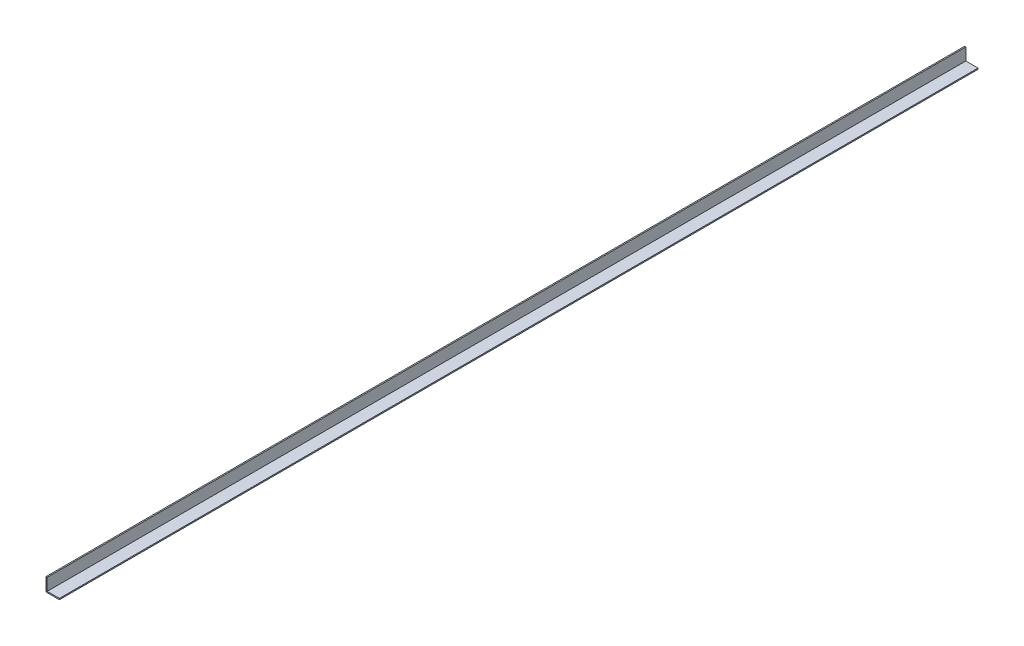
SolidWorks part; units mm, degrees
material "ASTM A36 Acero"
ref_plane "Alzado" through (0, 0, 0) normal (0, 0, 1) x (1, 0, 0)
ref_plane "Planta" through (0, 0, 0) normal (0, 1, 0) x (1, 0, 0)
ref_plane "Vista lateral" through (0, 0, 0) normal (1, 0, 0) x (0, 0, -1)
sketch "Croquis1" plane through (0, 0, 0) normal (0, 0, 1) x (1, 0, 0)
  line L0 (0, 88.9) -> (0, 0)
  line L1 (0, 0) -> (88.9, 0)
  line L2 (88.9, 0) -> (88.9, 7.94)
  line L3 (88.9, 7.94) -> (7.94, 7.94)
  line L4 (7.94, 7.94) -> (7.94, 88.9)
  line L5 (7.94, 88.9) -> (0, 88.9)
  dimension "D1" = 7.94
  dimension "D2" = 88.9
extrude "Saliente-Extruir1" add sketch "Croquis1" against normal blind 6100
